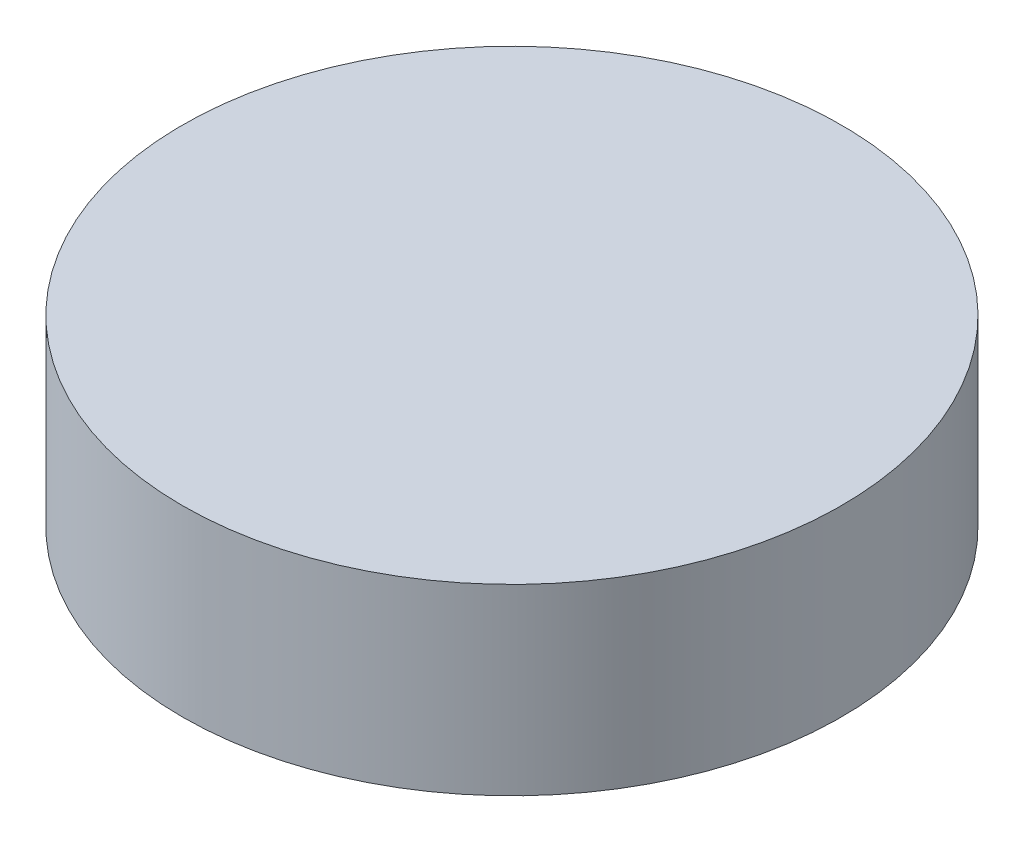
SolidWorks part; units mm, degrees
ref_plane "Front Plane" through (0, 0, 0) normal (0, 0, 1) x (1, 0, 0)
ref_plane "Top Plane" through (0, 0, 0) normal (0, 1, 0) x (1, 0, 0)
ref_plane "Right Plane" through (0, 0, 0) normal (1, 0, 0) x (0, 0, -1)
sketch "Sketch1" plane through (0, 0, 0) normal (0, 1, 0) x (1, 0, 0)
  circle A0 centre (4.9997, -4.9619) radius 11.43
  dimension "D1" = 22.86
extrude "Boss-Extrude1" add sketch "Sketch1" along normal blind 6.35
